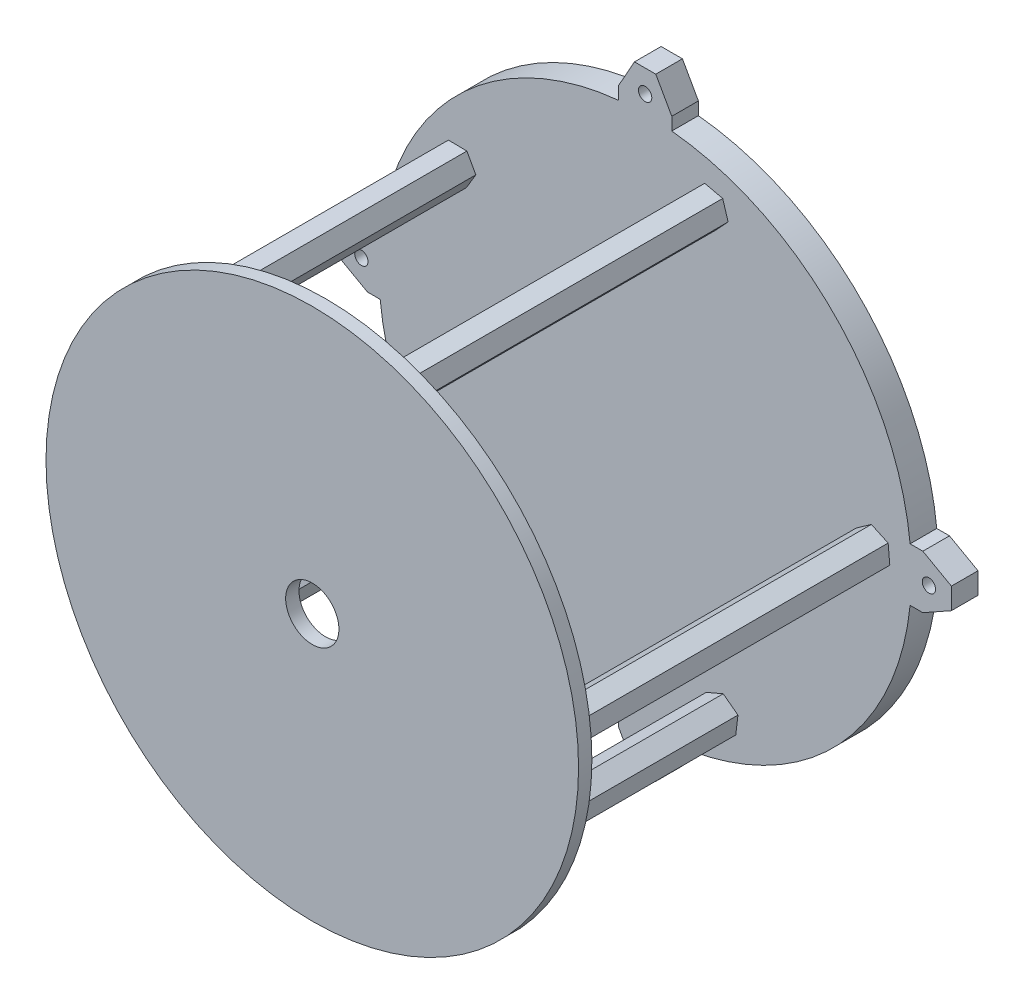
SolidWorks part; units mm, degrees
ref_plane "Front Plane" through (0, 0, 0) normal (0, 0, 1) x (1, 0, 0)
ref_plane "Top Plane" through (0, 0, 0) normal (0, 1, 0) x (1, 0, 0)
ref_plane "Right Plane" through (0, 0, 0) normal (1, 0, 0) x (0, 0, -1)
sketch "Sketch1" plane through (0, 0, 0) normal (0, 0, 1) x (1, 0, 0)
  line L0 (0, 0) -> (0, 134.2822) construction
  line L1 (-4, 115) -> (4, 115)
  line L2 (-4, 115) -> (-10, 104.2923)
  line L3 (-10, 104.2923) -> (-10, 99.4987)
  line L4 (10, 104.2923) -> (10, 99.4987)
  line L5 (4, 115) -> (10, 104.2923)
  line L6 (115, 4) -> (104.2923, 10)
  line L7 (115, -4) -> (104.2923, -10)
  line L8 (104.2923, -10) -> (99.4987, -10)
  line L9 (104.2923, 10) -> (99.4987, 10)
  line L10 (4, -115) -> (10, -104.2923)
  line L11 (-4, -115) -> (-10, -104.2923)
  line L12 (-10, -104.2923) -> (-10, -99.4987)
  line L13 (10, -104.2923) -> (10, -99.4987)
  line L14 (-115, -4) -> (-104.2923, -10)
  line L15 (-115, 4) -> (-104.2923, 10)
  line L16 (-104.2923, 10) -> (-99.4987, 10)
  line L17 (-104.2923, -10) -> (-99.4987, -10)
  line L18 (115, 4) -> (115, -4)
  line L19 (-115, 4) -> (-115, -4)
  line L20 (-4, -115) -> (4, -115)
  circle A0 centre (0, 0) radius 100
  circle A1 centre (0, 106.5627) radius 2.5
  circle A2 centre (106.5627, 0) radius 2.5
  circle A3 centre (0, -106.5627) radius 2.5
  circle A4 centre (-106.5627, 0) radius 2.5
  point P7 (0, 115)
  point P40 (0, 0)
  dimension "D1" = 200
  dimension "D2" = 5
  dimension "D3" = 20
  dimension "D4" = 8
  dimension "D5" = 115
  dimension "D6" = 4
extrude "Boss-Extrude1" add sketch "Sketch1" along normal blind 10
sketch "Sketch2" plane through (0, 0, 10) normal (0, 0, 1) x (1, 0, 0)
  line L0 (-61.1832, -50.7057) -> (-65.7403, -45.4873)
  line L1 (34.0312, -84.8929) -> (34.8599, -78.0145)
  line L2 (34.8599, -78.0145) -> (29.3173, -73.8576)
  line L3 (29.3173, -73.8576) -> (22.9461, -76.5791)
  line L4 (22.9461, -76.5791) -> (22.1173, -83.4576)
  line L5 (22.1173, -83.4576) -> (27.6599, -87.6145)
  line L6 (27.6599, -87.6145) -> (34.0312, -84.8929)
  line L7 (-65.7403, -45.4873) -> (-72.5382, -46.8247)
  line L8 (-72.5382, -46.8247) -> (-74.7789, -53.3805)
  line L9 (-74.7789, -53.3805) -> (-70.2218, -58.5989)
  line L10 (-70.2218, -58.5989) -> (-63.4239, -57.2615)
  line L11 (-63.4239, -57.2615) -> (-61.1832, -50.7057)
  line L12 (-67.1306, 42.5197) -> (-63.5758, 48.4664)
  line L13 (-63.5758, 48.4664) -> (-66.9484, 54.5183)
  line L14 (-66.9484, 54.5183) -> (-73.8758, 54.6235)
  line L15 (-73.8758, 54.6235) -> (-77.4306, 48.6768)
  line L16 (-77.4306, 48.6768) -> (-74.058, 42.6249)
  line L17 (-74.058, 42.6249) -> (-67.1306, 42.5197)
  line L18 (19.6942, 76.9843) -> (26.4483, 75.4412)
  line L19 (26.4483, 75.4412) -> (31.1618, 80.5188)
  line L20 (31.1618, 80.5188) -> (29.1212, 87.1397)
  line L21 (29.1212, 87.1397) -> (22.367, 88.6829)
  line L22 (22.367, 88.6829) -> (17.6535, 83.6052)
  line L23 (17.6535, 83.6052) -> (19.6942, 76.9843)
  line L24 (79.3023, 5.0592) -> (79.9218, -1.8412)
  line L25 (79.9218, -1.8412) -> (86.2075, -4.755)
  line L26 (86.2075, -4.755) -> (91.8737, -0.7682)
  line L27 (91.8737, -0.7682) -> (91.2542, 6.1322)
  line L28 (91.2542, 6.1322) -> (84.9685, 9.0459)
  line L29 (84.9685, 9.0459) -> (79.3023, 5.0592)
  circle A0 centre (28.4886, -80.736) radius 6 construction
  point P29 (0, 0)
  dimension "D1" = 12
  dimension "D2" = 5
extrude "Boss-Extrude2" add sketch "Sketch2" along normal blind 120
sketch "Sketch3" plane through (0, 0, 130) normal (0, 0, 1) x (1, 0, 0)
  circle A0 centre (0, 0) radius 100
  circle A1 centre (0, 0) radius 10
  dimension "D1" = 20
extrude "Boss-Extrude3" add sketch "Sketch3" along normal blind 5
